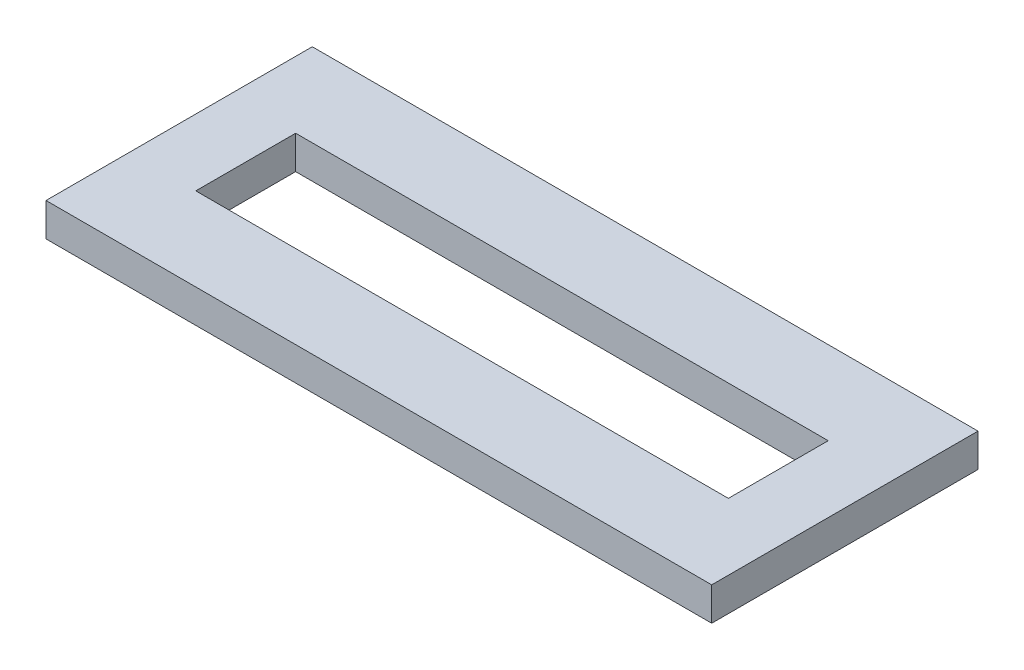
SolidWorks part; units mm, degrees
ref_plane "Front Plane" through (0, 0, 0) normal (0, 0, 1) x (1, 0, 0)
ref_plane "Top Plane" through (0, 0, 0) normal (0, 1, 0) x (1, 0, 0)
ref_plane "Right Plane" through (0, 0, 0) normal (1, 0, 0) x (0, 0, -1)
sketch "Sketch1" plane through (0, 0, 0) normal (0, 1, 0) x (1, 0, 0)
  line L1 (-31.75, 12.7) -> (31.75, 12.7)
  line L2 (-31.75, 12.7) -> (-31.75, -12.7)
  line L3 (-31.75, -12.7) -> (31.75, -12.7)
  line L4 (31.75, 12.7) -> (31.75, -12.7)
  line L7 (25.4, 4.7625) -> (25.4, -4.7625)
  line L8 (0, -4.7625) -> (0, -5.9534) construction
  line L9 (-25.4, 4.7625) -> (-25.4, -4.7625)
  line L10 (-25.4, 4.7625) -> (25.4, 4.7625)
  line L11 (25.4, -4.7625) -> (-25.4, -4.7625)
  point P0 (0, 0)
  point P9 (0, 0)
  dimension "D1" = 63.5
  dimension "D2" = 25.4
extrude "Boss-Extrude1" add sketch "Sketch1" along normal blind 3.175
